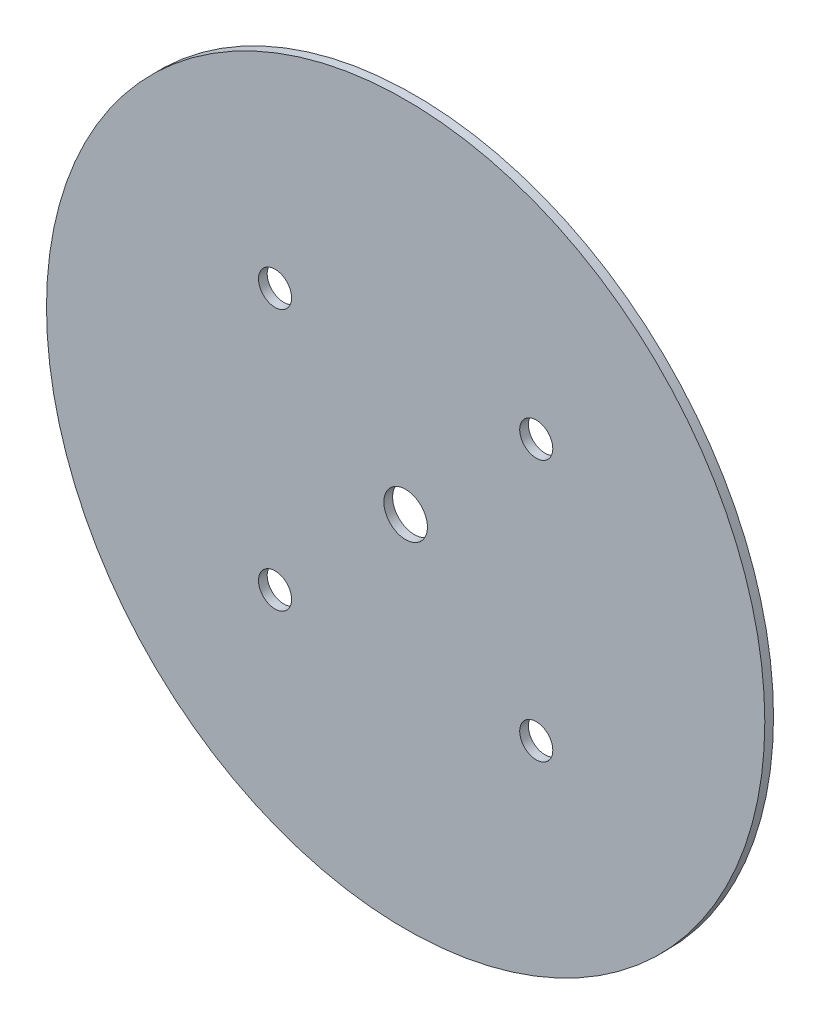
SolidWorks part; units mm, degrees
material "1060 合金"
ref_plane "前视基准面" through (0, 0, 0) normal (0, 0, 1) x (1, 0, 0)
ref_plane "上视基准面" through (0, 0, 0) normal (0, 1, 0) x (1, 0, 0)
ref_plane "右视基准面" through (0, 0, 0) normal (1, 0, 0) x (0, 0, -1)
sketch "草图1" plane through (0, 0, 0) normal (0, 0, 1) x (1, 0, 0)
  circle A0 centre (0, 0) radius 82.5
  dimension "D1" = 165
extrude "凸台-拉伸1" add sketch "草图1" along normal blind 2
sketch "草图2" plane through (0, 0, 2) normal (0, 0, 1) x (1, 0, 0)
  line L0 (0, 30) -> (0, 0) construction
  line L1 (0, 0) -> (0, -30) construction
  line L2 (-34, 0) -> (0, 0) construction
  line L3 (0, 0) -> (30, 0) construction
  circle A4 centre (30, 30) radius 3.8
  circle A5 centre (-30, 30) radius 3.8
  circle A6 centre (-30, -30) radius 3.8
  circle A7 centre (30, -30) radius 3.8
  circle A8 centre (0, 0) radius 5
  dimension "D1" = 7.6
  dimension "D2" = 7.6
  dimension "D7" = 10
  dimension "D3" = 7.6
  dimension "D4" = 7.6
  dimension "D5" = 60
  dimension "D6" = 60
extrude "切除-拉伸1" cut sketch "草图2" against normal through all
